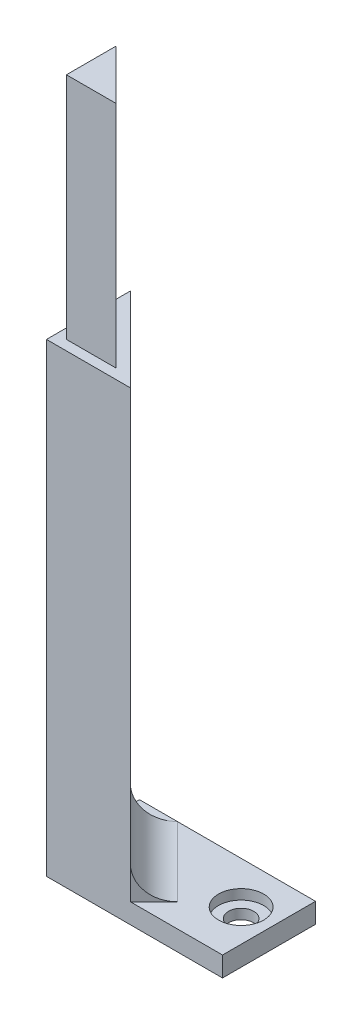
SolidWorks part; units mm, degrees
ref_plane "Front Plane" through (0, 0, 0) normal (0, 0, 1) x (1, 0, 0)
ref_plane "Top Plane" through (0, 0, 0) normal (0, 1, 0) x (1, 0, 0)
ref_plane "Right Plane" through (0, 0, 0) normal (1, 0, 0) x (0, 0, -1)
sketch "Sketch1" plane through (0, 0, 0) normal (0, 1, 0) x (1, 0, 0)
  line L9 (0, 0) -> (0, 15)
  line L35 (0, 0) -> (15, 0)
  line L50 (0, 15) -> (15, 0)
  point P0 (0, 0)
  point P5 (0, 0)
  point P6 (0, 0)
  point P9 (0, 0)
  point P10 (0, 0)
  dimension "D1" = 15
  dimension "D2" = 15
extrude "Boss-Extrude3" add sketch "Sketch1" along normal blind 320
sketch "Sketch7" plane through (0, 0, 0) normal (0, 0, 1) x (1, 0, 0)
  line L0 (15, 320) -> (0, 320)
  line L1 (0, 320) -> (0, 209)
  line L2 (0, 320) -> (0, 0) construction
  line L3 (0, 0) -> (15, 0) construction
  line L4 (15, 320) -> (15, 209)
  line L5 (15, 320) -> (15, 0) construction
  line L6 (15, 209) -> (0, 209)
  dimension "D1" = 209
extrude "Cut-Extrude3" cut sketch "Sketch7" against normal through all
sketch "Sketch8" plane through (0, 0, 0) normal (0, -1, 0) x (1, 0, 0)
  line L3 (-3, -22.2426) -> (-3, 3)
  line L4 (-3, 3) -> (22.2426, 3)
  line L5 (22.2426, 3) -> (-3, -22.2426)
extrude "Boss-Extrude5" add sketch "Sketch8" against normal blind 140
sketch "Sketch4" plane through (0, 0, 0) normal (0, -1, 0) x (1, 0, 0)
  line L0 (-3, 3) -> (-3, -25)
  line L6 (50, 0) -> (50, -25)
  line L9 (-3, -25) -> (50, -25)
  line L10 (-3, 3) -> (50, 3)
  line L11 (50, 3) -> (50, -25)
  circle A0 centre (40.3, -12.3) radius 3.8
  dimension "D3" = 7.6
  dimension "D5" = 12.7
  dimension "D6" = 43.3
  dimension "D1" = 28
  dimension "D2" = 53
  dimension "D4" = 25
extrude "Boss-Extrude4" add sketch "Sketch4" against normal blind 6
sketch "Sketch9" plane through (0, 6, 0) normal (0, 1, 0) x (1, 0, 0)
  line L0 (22.2426, -3) -> (29.3137, 4.0711)
  line L1 (29.3137, 4.0711) -> (8.3848, 25)
  line L2 (-3, 25) -> (50, 25) construction
  line L3 (8.3848, 25) -> (1.3137, 17.9289)
  line L4 (-3, 22.2426) -> (22.2426, -3) construction
  line L5 (1.3137, 17.9289) -> (22.2426, -3)
  dimension "D1" = 10
extrude "Boss-Extrude6" add sketch "Sketch9" along normal blind 10
sketch "Sketch10" plane through (12.6213, 0, 12.6213) normal (0.7071, 0, 0.7071) x (0.7071, 0, -0.7071)
  line L0 (13.6066, 16) -> (23.6066, 16)
  line L1 (23.6066, 16) -> (23.6066, 6)
  arc A0 (13.6066, 16) -> (23.6066, 6) centre (23.6066, 16) ccw
extrude "Cut-Extrude4" cut sketch "Sketch10" against normal through all
sketch "Sketch11" plane through (0, 6, 0) normal (0, 1, 0) x (1, 0, 0)
  circle A0 centre (40.3, 12.3) radius 6.8
  circle A1 centre (40.3, 12.3) radius 3.8 construction
  dimension "D1" = 3
extrude "Cut-Extrude5" cut sketch "Sketch11" against normal blind 3
